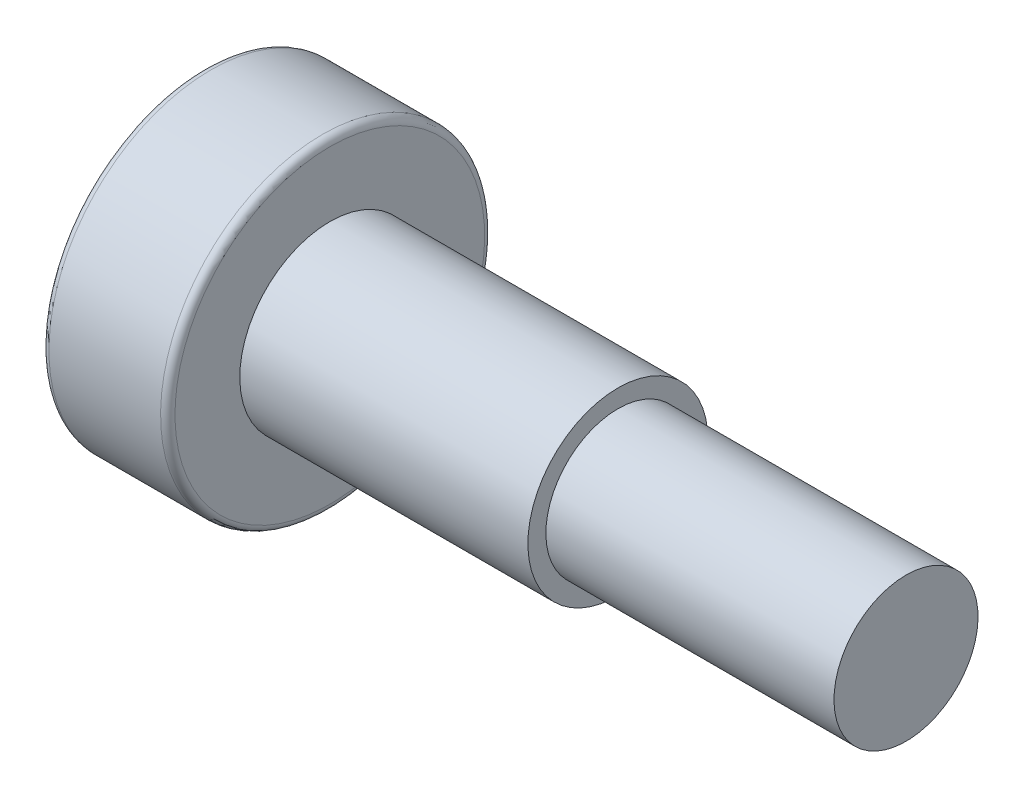
SolidWorks part; units mm, degrees
material "AISI 304"
ref_plane "前视基准面" through (0, 0, 0) normal (0, 0, 1) x (1, 0, 0)
ref_plane "上视基准面" through (0, 0, 0) normal (0, 1, 0) x (1, 0, 0)
ref_plane "右视基准面" through (0, 0, 0) normal (1, 0, 0) x (0, 0, -1)
sketch "草图1" plane through (0, 0, 0) normal (0, 0, 1) x (1, 0, 0)
  line L0 (0, 0) -> (0, 4.5)
  line L1 (0, 4.5) -> (3.5, 4.5)
  line L2 (3.5, 4.5) -> (3.5, 2.5)
  line L3 (3.5, 2.5) -> (11.5, 2.5)
  line L4 (11.5, 2.5) -> (11.5, 2)
  line L5 (11.5, 2) -> (19.5, 2)
  line L6 (19.5, 2) -> (19.5, 0)
  line L7 (19.5, 0) -> (0, 0) construction
  line L8 (0, 0) -> (19.5, 0)
  dimension "D1" = 9
  dimension "D2" = 5
  dimension "D3" = 4
  dimension "D4" = 3.5
  dimension "D5" = 8
  dimension "D6" = 8
revolve "旋转1" add sketch "草图1" angle 360 about L7
cosmetic thread "装饰螺纹线1"
sketch "草图2" plane through (0, 0, 0) normal (-1, 0, 0) x (0, 0, 1)
  line L1 (1.5, 0.866) -> (0, 1.7321)
  line L2 (0, 1.7321) -> (-1.5, 0.866)
  line L3 (-1.5, 0.866) -> (-1.5, -0.866)
  line L4 (-1.5, -0.866) -> (0, -1.7321)
  line L5 (0, -1.7321) -> (1.5, -0.866)
  line L6 (1.5, -0.866) -> (1.5, 0.866)
  circle A0 centre (0, 0) radius 1.5 construction
  dimension "D1" = 3
extrude "切除-拉伸1" cut sketch "草图2" against normal blind 2
fillet "圆角1" radius 0.2 2 edges at (0, 4.5, 0) (3.5, 4.5, 0)
